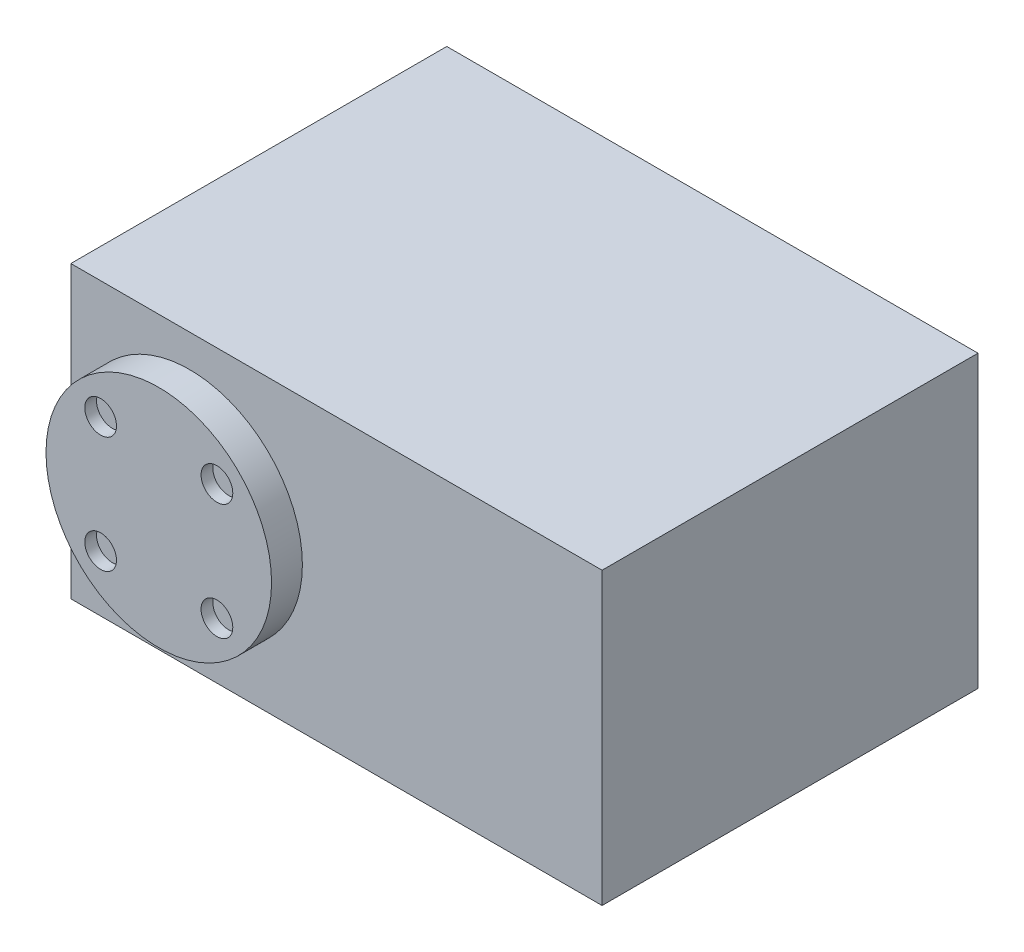
SolidWorks part; units mm, degrees
ref_plane "Front Plane" through (0, 0, 0) normal (0, 0, 1) x (1, 0, 0)
ref_plane "Top Plane" through (0, 0, 0) normal (0, 1, 0) x (1, 0, 0)
ref_plane "Right Plane" through (0, 0, 0) normal (1, 0, 0) x (0, 0, -1)
ref_plane "PZ_m16_000" through (0, 0, -16) normal (0, 0, 1) x (1, 0, 0)
sketch "S_box1" plane through (0, 0, -16) normal (0, 0, 1) x (1, 0, 0)
  line L0 (-10.11, -12.36) -> (35.11, -12.36)
  line L1 (35.11, -12.36) -> (35.11, 12.36)
  line L2 (35.11, 12.36) -> (-10.11, 12.36)
  line L3 (-10.11, 12.36) -> (-10.11, -12.36)
  dimension "P1" = 10.11
  dimension "P2" = 12.36
  dimension "P3" = 35.11
  dimension "P4" = 12.36
  dimension "P5" = 35.11
  dimension "P6" = 12.36
  dimension "P7" = 10.11
  dimension "P8" = 12.36
extrude "Boss_1" add sketch "S_box1" along normal blind 32
ref_plane "PZ_p15_500" through (0, 0, 15.5) normal (0, 0, 1) x (1, 0, 0)
sketch "S_cyl2" plane through (0, 0, 15.5) normal (0, 0, 1) x (1, 0, 0)
  circle A0 centre (0, 0) radius 9.6
  dimension "D1_S_cyl2" = 19.2
extrude "Boss_2" add sketch "S_cyl2" along normal blind 3.125
ref_plane "PZ_m18_625" through (0, 0, -18.625) normal (0, 0, 1) x (1, 0, 0)
sketch "S_cyl3" plane through (0, 0, -18.625) normal (0, 0, 1) x (1, 0, 0)
  circle A0 centre (0, 0) radius 9.6
  dimension "D1_S_cyl3" = 19.2
extrude "Boss_3" add sketch "S_cyl3" along normal blind 3.125
ref_plane "PZ_p17_625" through (0, 0, 17.625) normal (0, 0, 1) x (1, 0, 0)
sketch "S_hole4" plane through (0, 0, 17.625) normal (0, 0, 1) x (1, 0, 0)
  circle A0 centre (4.9497, 4.9497) radius 1.35
  dimension "D1_S_hole4" = 2.7
  dimension "P2" = 4.9497
  dimension "P3" = 4.9497
extrude "Hole_4" cut sketch "S_hole4" along normal blind 1.1
sketch "S_hole5" plane through (0, 0, 17.625) normal (0, 0, 1) x (1, 0, 0)
  circle A0 centre (-4.9497, 4.9497) radius 1.35
  dimension "D1_S_hole5" = 2.7
  dimension "P2" = 4.9497
  dimension "P3" = 4.9497
extrude "Hole_5" cut sketch "S_hole5" along normal blind 1.1
sketch "S_hole6" plane through (0, 0, 17.625) normal (0, 0, 1) x (1, 0, 0)
  circle A0 centre (-4.9497, -4.9497) radius 1.35
  dimension "D1_S_hole6" = 2.7
  dimension "P2" = 4.9497
  dimension "P3" = 4.9497
extrude "Hole_6" cut sketch "S_hole6" along normal blind 1.1
sketch "S_hole7" plane through (0, 0, 17.625) normal (0, 0, 1) x (1, 0, 0)
  circle A0 centre (4.9497, -4.9497) radius 1.35
  dimension "D1_S_hole7" = 2.7
  dimension "P2" = 4.9497
  dimension "P3" = 4.9497
extrude "Hole_7" cut sketch "S_hole7" along normal blind 1.1
equation "\"plate_t\" = 3"
equation "\"clearance\" = 0.4"
